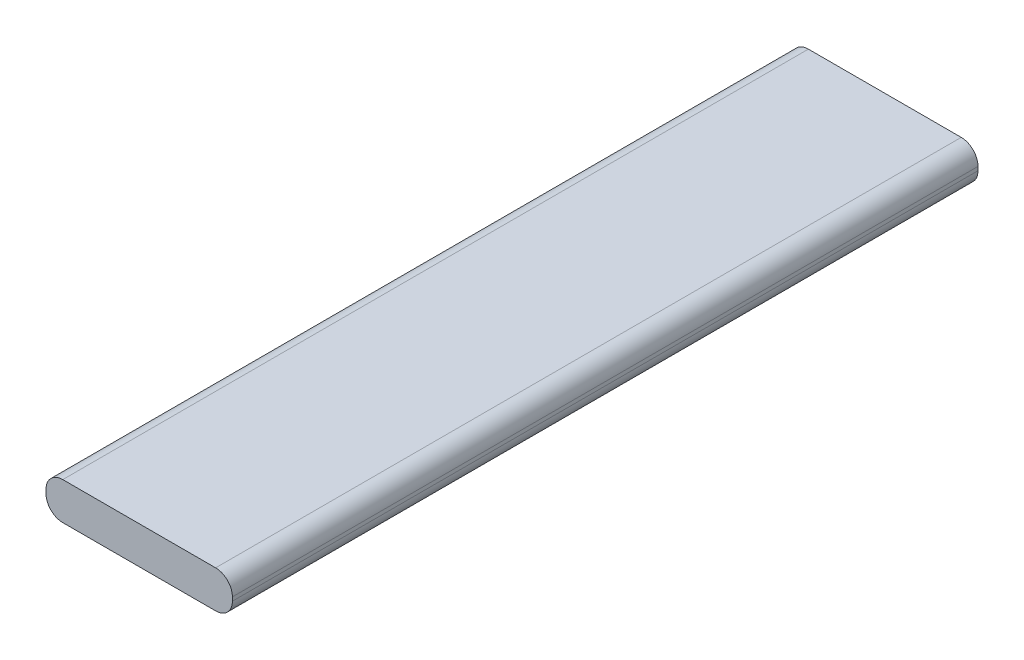
SolidWorks part; units mm, degrees
material "ABS PC"
ref_plane "Front Plane" through (0, 0, 0) normal (0, 0, 1) x (1, 0, 0)
ref_plane "Top Plane" through (0, 0, 0) normal (0, 1, 0) x (1, 0, 0)
ref_plane "Right Plane" through (0, 0, 0) normal (1, 0, 0) x (0, 0, -1)
sketch "Sketch1" plane through (0, 0, 0) normal (0, 0, 1) x (1, 0, 0)
  line L1 (-2.05, 0.5) -> (2.05, 0.5)
  line L2 (-2.5, 0.05) -> (-2.5, -0.05)
  line L3 (-2.05, -0.5) -> (2.05, -0.5)
  line L4 (2.5, 0.05) -> (2.5, -0.05)
  line L5 (-2.5, 0.5) -> (2.5, -0.5) construction
  line L6 (-2.5, -0.5) -> (2.5, 0.5) construction
  arc A0 (2.05, 0.5) -> (2.5, 0.05) centre (2.05, 0.05) cw
  arc A1 (2.05, -0.5) -> (2.5, -0.05) centre (2.05, -0.05) ccw
  arc A2 (-2.5, -0.05) -> (-2.05, -0.5) centre (-2.05, -0.05) ccw
  arc A3 (-2.05, 0.5) -> (-2.5, 0.05) centre (-2.05, 0.05) ccw
  point P0 (0, 0)
  dimension "D1" = 0.45
extrude "Boss-Extrude1" add sketch "Sketch1" along normal blind 20
